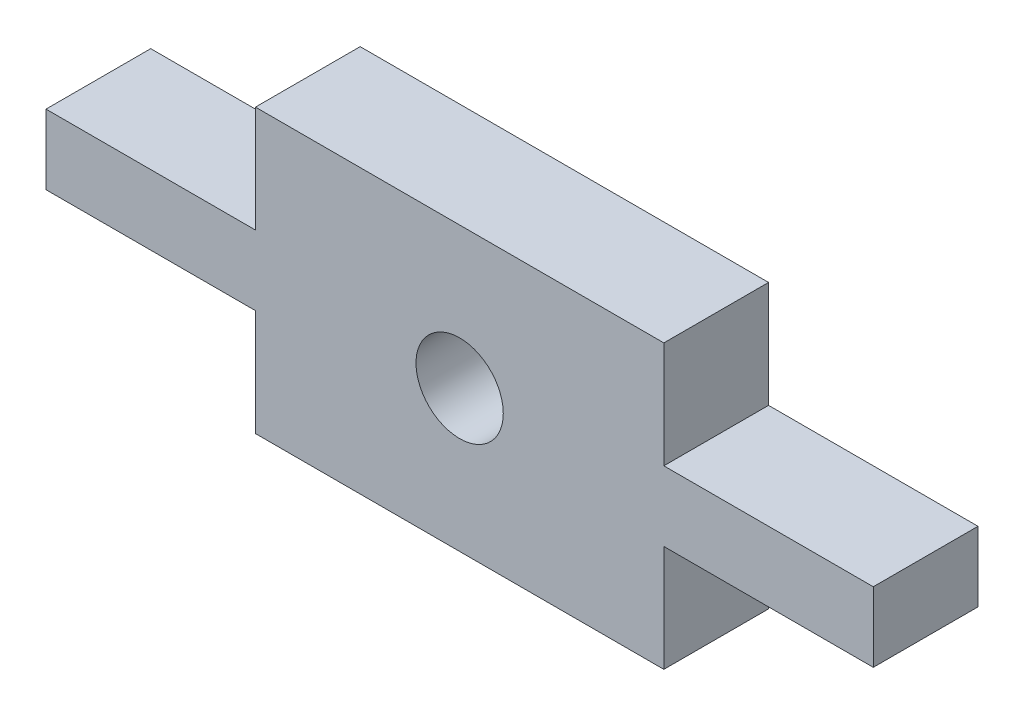
SolidWorks part; units mm, degrees
ref_plane "Front Plane" through (0, 0, 0) normal (0, 0, 1) x (1, 0, 0)
ref_plane "Top Plane" through (0, 0, 0) normal (0, 1, 0) x (1, 0, 0)
ref_plane "Right Plane" through (0, 0, 0) normal (1, 0, 0) x (0, 0, -1)
sketch "Sketch1" plane through (0, 0, 0) normal (0, 0, 1) x (1, 0, 0)
  line L0 (-5.85, -4.05) -> (5.85, 4.05) construction
  line L5 (-5.85, 4.05) -> (5.85, -4.05) construction
  line L28 (-5.85, -1) -> (-5.85, -4.05)
  line L29 (-5.85, -4.05) -> (5.85, -4.05)
  line L30 (5.85, -4.05) -> (5.85, -1)
  line L31 (5.85, -1) -> (11.85, -1)
  line L32 (11.85, -1) -> (11.85, 1)
  line L33 (11.85, 1) -> (5.85, 1)
  line L34 (5.85, 1) -> (5.85, 4.05)
  line L35 (5.85, 4.05) -> (-5.85, 4.05)
  line L36 (-5.85, 4.05) -> (-5.85, 1)
  line L37 (-5.85, 1) -> (-11.85, 1)
  line L38 (-11.85, 1) -> (-11.85, -1)
  line L39 (-11.85, -1) -> (-5.85, -1)
  circle A1 centre (0, 0) radius 1.25
  point P4 (0, 0)
  dimension "D4" = 2.5
  dimension "D2" = 11.7
  dimension "D3" = 8.1
  dimension "D5" = 6
  dimension "D6" = 3.05
extrude "Boss-Extrude1" add sketch "Sketch1" along normal blind 3 contours L35 L36 L37 L38 L39 L28 L29 L30 L31 L32 L33 L34
